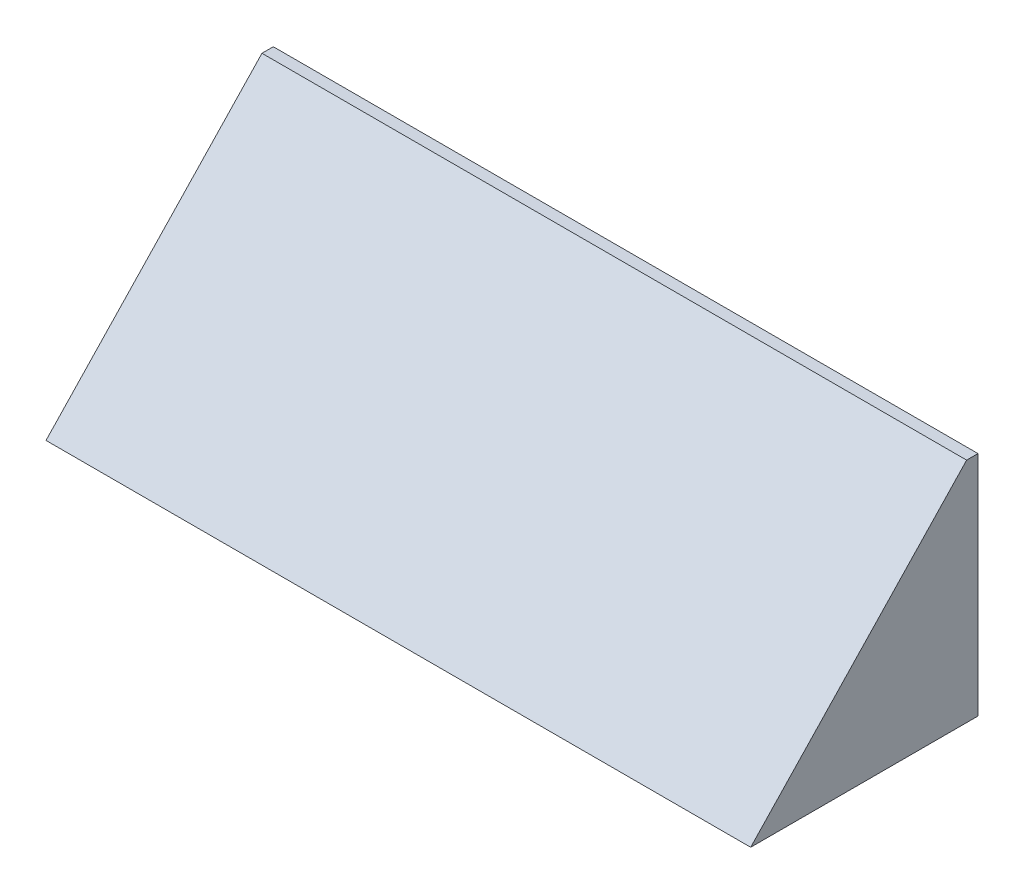
SolidWorks part; units mm, degrees
ref_plane "Front Plane" through (0, 0, 0) normal (0, 0, 1) x (1, 0, 0)
ref_plane "Top Plane" through (0, 0, 0) normal (0, 1, 0) x (1, 0, 0)
ref_plane "Right Plane" through (0, 0, 0) normal (1, 0, 0) x (0, 0, -1)
ref_plane "Plane1" through (0, 20, 0) normal (0, 1, 0) x (1, 0, 0)
sketch "Sketch1" plane through (0, 0, 0) normal (0, 1, 0) x (1, 0, 0)
  line L0 (-31.1995, 24.8511) -> (30.8005, 24.8511)
  line L1 (30.8005, 24.8511) -> (30.8005, 4.8511)
  line L2 (30.8005, 4.8511) -> (-31.1995, 4.8511)
  line L3 (-31.1995, 4.8511) -> (-31.1995, 24.8511)
sketch "Sketch2" plane through (0, 20, 0) normal (0, 1, 0) x (1, 0, 0)
  line L0 (-31.1995, 24.8511) -> (30.8005, 24.8511)
  line L1 (-31.1995, 24.8511) -> (-31.1995, 23.8511)
  line L2 (-31.1995, 23.8511) -> (30.8005, 23.8511)
  line L3 (30.8005, 24.8511) -> (30.8005, 4.8511) construction
  line L4 (30.8005, 23.8511) -> (30.8005, 24.8511)
loft "Loft2" add profiles "Sketch1", "Sketch2"
shell "Shell1" thickness 1
